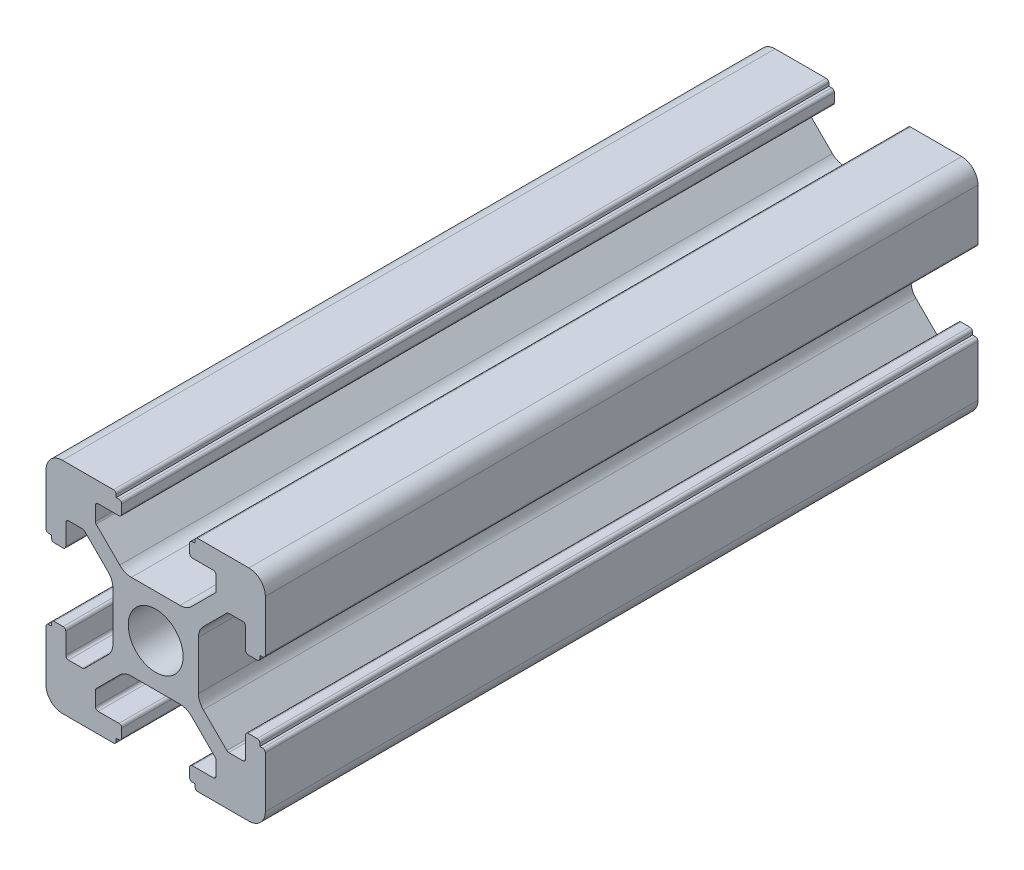
SolidWorks part; units mm, degrees
ref_plane "前视基准面" through (0, 0, 0) normal (0, 0, 1) x (1, 0, 0)
ref_plane "上视基准面" through (0, 0, 0) normal (0, 1, 0) x (1, 0, 0)
ref_plane "右视基准面" through (0, 0, 0) normal (1, 0, 0) x (0, 0, -1)
sketch "草图1" plane through (0, 0, 0) normal (0, 0, 1) x (1, 0, 0)
  line L0 (0, 0) -> (0, 5.5) construction
  line L1 (-8.5023, -10.0023) -> (-3.85, -10.0023)
  line L2 (-10.0023, -8.5023) -> (-10.0023, -3.85)
  line L3 (-8.5023, 10.0023) -> (-3.85, 10.0023)
  line L4 (10.0023, -8.5023) -> (10.0023, -3.85)
  line L5 (-10.0023, -10.0023) -> (10.0023, 10.0023) construction
  line L6 (-10.0023, 10.0023) -> (10.0023, -10.0023) construction
  line L7 (-2.218, -3.9) -> (2.218, -3.9)
  line L8 (-3.9, -2.218) -> (-3.9, 2.218)
  line L9 (-2.218, 3.9) -> (2.218, 3.9)
  line L10 (3.9, -2.218) -> (3.9, 2.218)
  line L11 (-3.9, -3.9) -> (3.9, 3.9) construction
  line L12 (-3.9, 3.9) -> (3.9, -3.9) construction
  line L13 (-5.25, -8.2) -> (-3.35, -8.2)
  line L14 (-8.2, -5.25) -> (-8.2, -3.35)
  line L15 (-5.25, 8.2) -> (-3.35, 8.2)
  line L16 (8.2, -5.25) -> (8.2, -3.35)
  line L17 (-8.2, -8.2) -> (8.2, 8.2) construction
  line L18 (-8.2, 8.2) -> (8.2, -8.2) construction
  line L19 (-7.95, 5.5) -> (-6.6642, 5.5)
  line L20 (0, 0) -> (5.5, 0) construction
  line L23 (-5.5, 7.95) -> (-5.5, 6.6642)
  line L26 (0, 0) -> (-0.5303, 0.5303)
  line L27 (3.2787, 4.3393) -> (5.4268, 6.4874)
  line L28 (0, 0) -> (0.5303, -0.5303)
  line L29 (5.5, 6.6642) -> (5.5, 7.95)
  line L30 (4.3393, 3.2787) -> (6.4874, 5.4268)
  line L31 (6.6642, 5.5) -> (7.95, 5.5)
  line L32 (4.3393, -3.2787) -> (6.4874, -5.4268)
  line L33 (3.2787, -4.3393) -> (5.4268, -6.4874)
  line L34 (-3.2787, -4.3393) -> (-5.4268, -6.4874)
  line L35 (-4.3393, -3.2787) -> (-6.4874, -5.4268)
  line L36 (-4.3393, 3.2787) -> (-6.4874, 5.4268)
  line L37 (-3.2787, 4.3393) -> (-5.4268, 6.4874)
  line L38 (3.1, -8.45) -> (3.1, -9.2523)
  line L39 (8.45, 3.1) -> (9.2523, 3.1)
  line L40 (-5.5, -6.6642) -> (-5.5, -7.95)
  line L41 (-6.6642, -5.5) -> (-7.95, -5.5)
  line L42 (5.5, -6.6642) -> (5.5, -7.95)
  line L43 (6.6642, -5.5) -> (7.95, -5.5)
  line L44 (9.2523, -3.1) -> (8.45, -3.1)
  line L46 (10.0023, 3.85) -> (10.0023, 8.5023)
  line L47 (8.2, 3.35) -> (8.2, 5.25)
  line L48 (-3.1, -9.2523) -> (-3.1, -8.45)
  line L49 (-8.45, -3.1) -> (-9.2523, -3.1)
  line L50 (-9.2523, 3.1) -> (-8.45, 3.1)
  line L51 (-3.1, 8.45) -> (-3.1, 9.2523)
  line L52 (3.1, 9.2523) -> (3.1, 8.45)
  line L53 (3.85, 10.0023) -> (8.5023, 10.0023)
  line L54 (3.35, 8.2) -> (5.25, 8.2)
  line L55 (-10.0023, 3.85) -> (-10.0023, 8.5023)
  line L56 (-8.2, 3.35) -> (-8.2, 5.25)
  line L57 (3.35, -8.2) -> (5.25, -8.2)
  line L58 (3.85, -10.0023) -> (8.5023, -10.0023)
  line L59 (9.7523, -3.6) -> (9.5023, -3.6)
  line L61 (9.7523, 3.6) -> (9.5023, 3.6)
  line L62 (9.5023, -3.6) -> (9.5023, -3.35)
  line L63 (3.6, -9.7523) -> (3.6, -9.5023)
  line L64 (3.35, -9.5023) -> (3.6, -9.5023)
  line L65 (9.5023, 3.35) -> (9.5023, 3.6)
  line L66 (-3.6, -9.5023) -> (-3.35, -9.5023)
  line L67 (-3.6, -9.7523) -> (-3.6, -9.5023)
  line L68 (-9.7523, -3.6) -> (-9.5023, -3.6)
  line L69 (-9.5023, -3.35) -> (-9.5023, -3.6)
  line L70 (-9.5023, 3.6) -> (-9.5023, 3.35)
  line L71 (-9.7523, 3.6) -> (-9.5023, 3.6)
  line L72 (-3.6, 9.7523) -> (-3.6, 9.5023)
  line L73 (-3.35, 9.5023) -> (-3.6, 9.5023)
  line L74 (3.6, 9.5023) -> (3.35, 9.5023)
  line L75 (3.6, 9.7523) -> (3.6, 9.5023)
  circle A0 centre (0, 0) radius 2.5
  arc A1 (10.0023, 8.5023) -> (8.5023, 10.0023) centre (8.5023, 8.5023) ccw
  arc A2 (8.5023, -10.0023) -> (10.0023, -8.5023) centre (8.5023, -8.5023) ccw
  arc A3 (-10.0023, -8.5023) -> (-8.5023, -10.0023) centre (-8.5023, -8.5023) ccw
  arc A4 (-10.0023, 8.5023) -> (-8.5023, 10.0023) centre (-8.5023, 8.5023) cw
  arc A5 (-9.5023, -3.35) -> (-9.2523, -3.1) centre (-9.2523, -3.35) cw
  arc A6 (-9.7523, -3.6) -> (-10.0023, -3.85) centre (-9.7523, -3.85) ccw
  arc A7 (-8.45, -3.1) -> (-8.2, -3.35) centre (-8.45, -3.35) cw
  arc A8 (-7.95, -5.5) -> (-8.2, -5.25) centre (-7.95, -5.25) cw
  arc A9 (-6.4874, -5.4268) -> (-6.6642, -5.5) centre (-6.6642, -5.25) cw
  arc A10 (-5.4268, -6.4874) -> (-5.5, -6.6642) centre (-5.25, -6.6642) ccw
  arc A11 (-5.5, -7.95) -> (-5.25, -8.2) centre (-5.25, -7.95) ccw
  arc A12 (-3.6, -9.7523) -> (-3.85, -10.0023) centre (-3.85, -9.7523) cw
  arc A13 (-3.35, -9.5023) -> (-3.1, -9.2523) centre (-3.35, -9.2523) ccw
  arc A14 (-3.1, -8.45) -> (-3.35, -8.2) centre (-3.35, -8.45) ccw
  arc A15 (3.1, -8.45) -> (3.35, -8.2) centre (3.35, -8.45) cw
  arc A16 (5.5, -7.95) -> (5.25, -8.2) centre (5.25, -7.95) cw
  arc A17 (5.4268, -6.4874) -> (5.5, -6.6642) centre (5.25, -6.6642) cw
  arc A18 (6.4874, -5.4268) -> (6.6642, -5.5) centre (6.6642, -5.25) ccw
  arc A19 (7.95, -5.5) -> (8.2, -5.25) centre (7.95, -5.25) ccw
  arc A20 (8.45, -3.1) -> (8.2, -3.35) centre (8.45, -3.35) ccw
  arc A21 (9.5023, -3.35) -> (9.2523, -3.1) centre (9.2523, -3.35) ccw
  arc A22 (9.7523, -3.6) -> (10.0023, -3.85) centre (9.7523, -3.85) cw
  arc A23 (3.35, -9.5023) -> (3.1, -9.2523) centre (3.35, -9.2523) cw
  arc A24 (3.6, -9.7523) -> (3.85, -10.0023) centre (3.85, -9.7523) ccw
  arc A25 (7.95, 5.5) -> (8.2, 5.25) centre (7.95, 5.25) cw
  arc A26 (8.2, 3.35) -> (8.45, 3.1) centre (8.45, 3.35) ccw
  arc A27 (9.5023, 3.35) -> (9.2523, 3.1) centre (9.2523, 3.35) cw
  arc A28 (9.7523, 3.6) -> (10.0023, 3.85) centre (9.7523, 3.85) ccw
  arc A29 (6.6642, 5.5) -> (6.4874, 5.4268) centre (6.6642, 5.25) ccw
  arc A30 (5.4268, 6.4874) -> (5.5, 6.6642) centre (5.25, 6.6642) ccw
  arc A31 (5.5, 7.95) -> (5.25, 8.2) centre (5.25, 7.95) ccw
  arc A32 (3.1, 8.45) -> (3.35, 8.2) centre (3.35, 8.45) ccw
  arc A33 (3.6, 9.7523) -> (3.85, 10.0023) centre (3.85, 9.7523) cw
  arc A34 (3.35, 9.5023) -> (3.1, 9.2523) centre (3.35, 9.2523) ccw
  arc A35 (-9.7523, 3.6) -> (-10.0023, 3.85) centre (-9.7523, 3.85) cw
  arc A36 (-9.5023, 3.35) -> (-9.2523, 3.1) centre (-9.2523, 3.35) ccw
  arc A37 (-8.45, 3.1) -> (-8.2, 3.35) centre (-8.45, 3.35) ccw
  arc A38 (-8.2, 5.25) -> (-7.95, 5.5) centre (-7.95, 5.25) cw
  arc A39 (-6.4874, 5.4268) -> (-6.6642, 5.5) centre (-6.6642, 5.25) ccw
  arc A40 (-5.4268, 6.4874) -> (-5.5, 6.6642) centre (-5.25, 6.6642) cw
  arc A41 (-5.5, 7.95) -> (-5.25, 8.2) centre (-5.25, 7.95) cw
  arc A42 (-3.1, 8.45) -> (-3.35, 8.2) centre (-3.35, 8.45) cw
  arc A43 (-3.1, 9.2523) -> (-3.35, 9.5023) centre (-3.35, 9.2523) ccw
  arc A44 (-3.6, 9.7523) -> (-3.85, 10.0023) centre (-3.85, 9.7523) ccw
  arc A45 (-4.3393, 3.2787) -> (-3.9, 2.218) centre (-5.4, 2.218) cw
  arc A46 (-3.2787, 4.3393) -> (-2.218, 3.9) centre (-2.218, 5.4) ccw
  arc A47 (3.2787, 4.3393) -> (2.218, 3.9) centre (2.218, 5.4) cw
  arc A48 (4.3393, 3.2787) -> (3.9, 2.218) centre (5.4, 2.218) ccw
  arc A49 (4.3393, -3.2787) -> (3.9, -2.218) centre (5.4, -2.218) cw
  arc A50 (3.2787, -4.3393) -> (2.218, -3.9) centre (2.218, -5.4) ccw
  arc A51 (-4.3393, -3.2787) -> (-3.9, -2.218) centre (-5.4, -2.218) ccw
  arc A52 (-2.218, -3.9) -> (-3.2787, -4.3393) centre (-2.218, -5.4) ccw
  point P0 (0, 0)
  point P7 (10.0023, 0)
  point P62 (0, 0)
  point P76 (0, 0)
  point P92 (-8.2, -5.5)
  point P99 (0, 0)
  point P106 (-5.5, -8.2)
  point P117 (5.5, -8.2)
  point P124 (8.2, -5.5)
  point P137 (8.2, 5.5)
  point P140 (8.2, 3.1)
  point P147 (6.5607, 5.5)
  point P152 (5.5, 8.2)
  point P167 (-8.2, 5.5)
  point P174 (-5.5, 8.2)
  dimension "D1" = 1.5
  dimension "D5" = 0.25
  dimension "D6" = 1.5
  dimension "D2" = 4
  dimension "D3" = 4
  dimension "D4" = 4
extrude "凸台-拉伸1" add sketch "草图1" along normal blind 65 contours A52 L7 A50 L33 A17 L42 A16 L57 A15 L38 A23 L64 L63 A24 L58 A2 L4 A22 L59 L62 A21 L44 A20 L16 A19 L43 A18 L32 A49 L10 A48 L30 A29 L31 A25 L47 A26 L39 A27 L65 L61 A28 L46 A1 L53 A33 L75 L74 A34 L52 A32
